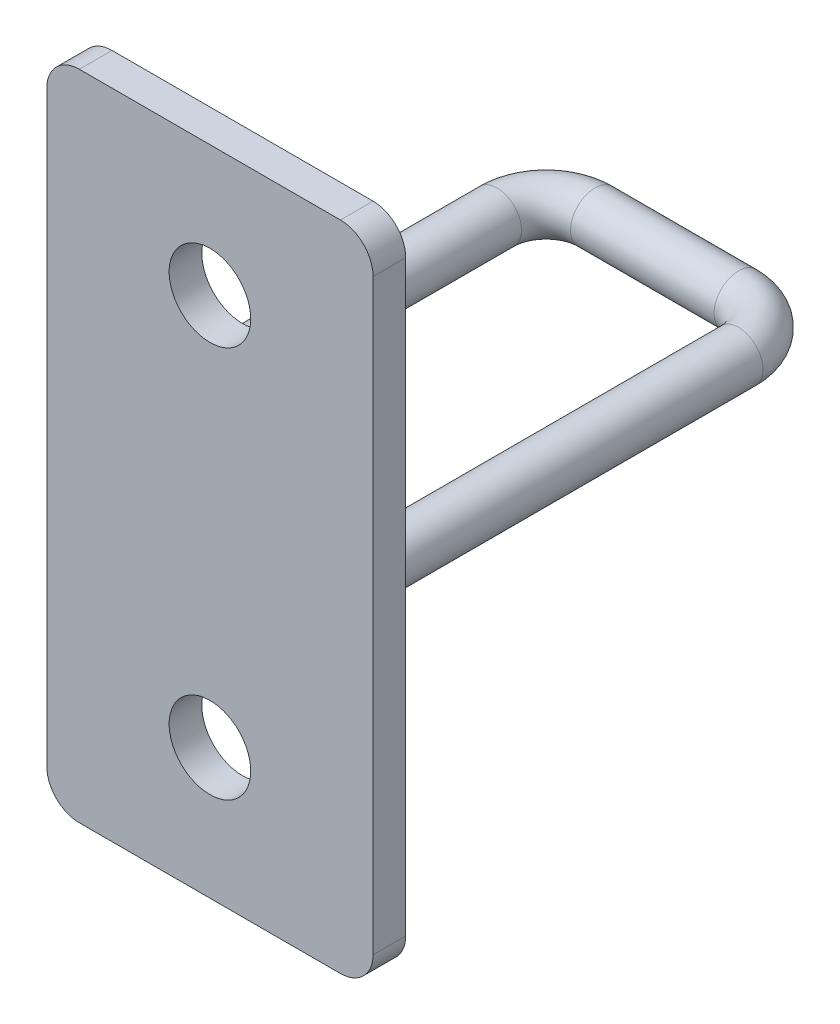
SolidWorks part; units mm, degrees
ref_plane "前视基准面" through (0, 0, 0) normal (0, 0, 1) x (1, 0, 0)
ref_plane "上视基准面" through (0, 0, 0) normal (0, 1, 0) x (1, 0, 0)
ref_plane "右视基准面" through (0, 0, 0) normal (1, 0, 0) x (0, 0, -1)
other "Configuration Table"
sketch "草图1" plane through (0, 0, 0) normal (0, 0, 1) x (1, 0, 0)
  line L1 (0, 0) -> (10, 0)
  line L2 (0, 0) -> (0, -20)
  line L3 (0, -20) -> (10, -20)
  line L4 (10, 0) -> (10, -20)
  circle A0 centre (5, -4) radius 1.25
  circle A1 centre (5, -16) radius 1.25
  point P9 (4.8571, -16)
  point P10 (0, 0)
  dimension "D5" = 2.5
  dimension "D6" = 2.5
  dimension "D7" = 5
  dimension "D1" = 10
  dimension "D2" = 20
  dimension "D3" = 12
  dimension "D4" = 4
  dimension "D8" = 5
extrude "凸台-拉伸1" add sketch "草图1" along normal blind 1
fillet "圆角1" radius 1 4 edges at (10, -20, 0.5) (0, -20, 0.5) (0, 0, 0.5) (10, 0, 0.5)
sketch "草图2" plane through (0, 0, 1) normal (0, 0, 1) x (1, 0, 0)
  line L0 (0, -1) -> (0, -19) construction
  line L1 (10, -19) -> (10, -1) construction
  circle A0 centre (1.3, -10) radius 0.75
  circle A1 centre (8.7, -10) radius 0.75
  dimension "D1" = 1.5
  dimension "D2" = 1.5
  dimension "D3" = 1.3
  dimension "D4" = 1.3
ref_plane "基准面1" through (0, -10, 0) normal (0, 1, 0) x (1, 0, 0)
sketch "草图5" plane through (0, -10, 0) normal (0, 1, 0) x (1, 0, 0)
  line L2 (1.3, 0) -> (1.3, 11.5)
  line L3 (2.8, 13) -> (7.2, 13)
  line L4 (8.7, 0) -> (8.7, 11.5)
  line L5 (9, 0) -> (1, 0) construction
  line L6 (0, -1) -> (0, 0) construction
  line L7 (10, 0) -> (10, -1) construction
  arc A0 (2.8, 13) -> (1.3, 11.5) centre (2.8, 11.5) ccw
  arc A1 (8.7, 11.5) -> (7.2, 13) centre (7.2, 11.5) ccw
  dimension "D3" = 3
  dimension "D4" = 3
  dimension "D1" = 1.3
  dimension "D2" = 1.3
  dimension "D5" = 13
sketch "草图13" plane through (0, 0, 0) normal (0, 0, -1) x (-1, 0, 0)
  circle A1 centre (-8.7, -10) radius 0.75 construction
  circle A3 centre (-8.7, -10) radius 0.75
sweep "扫描11" add profiles "草图13" path "草图5"
